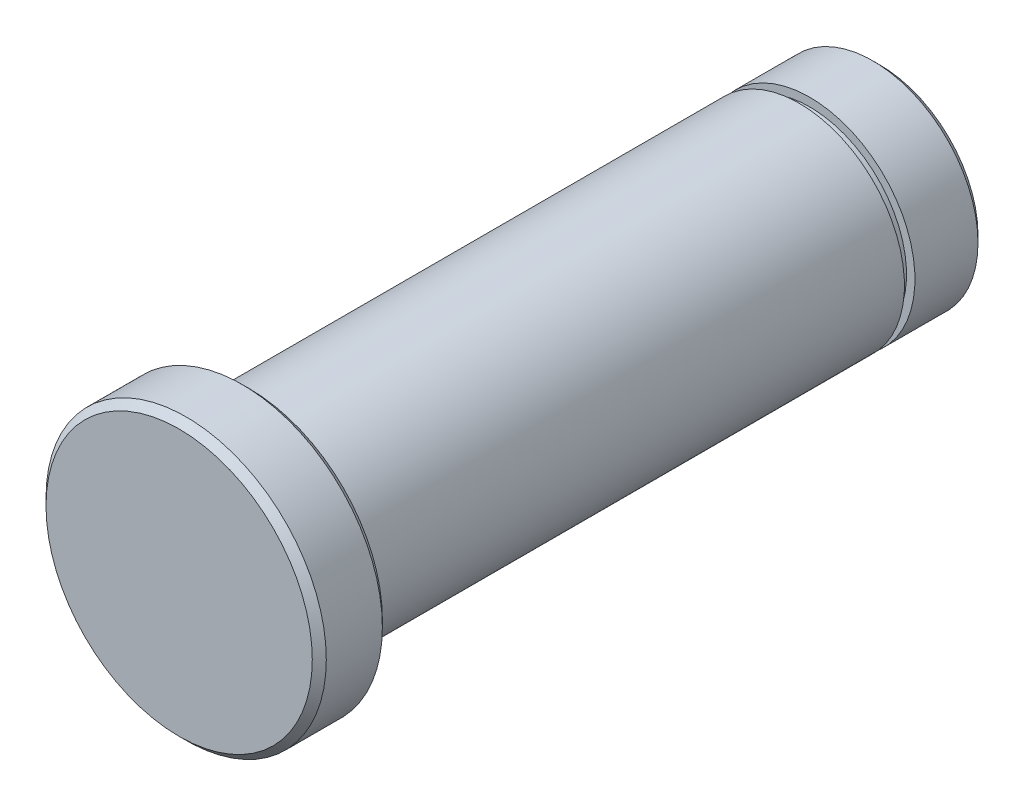
SolidWorks part; units mm, degrees
ref_plane "前视基准面" through (0, 0, 0) normal (0, 0, 1) x (1, 0, 0)
ref_plane "上视基准面" through (0, 0, 0) normal (0, 1, 0) x (1, 0, 0)
ref_plane "右视基准面" through (0, 0, 0) normal (1, 0, 0) x (0, 0, -1)
sketch "草图1" plane through (0, 0, 0) normal (0, 0, 1) x (1, 0, 0)
  circle A0 centre (0, 0) radius 15
  dimension "D1" = 30
extrude "凸台-拉伸1" add sketch "草图1" along normal blind 90
sketch "草图2" plane through (0, 0, 90) normal (0, 0, 1) x (1, 0, 0)
  circle A0 centre (0, 0) radius 20
  dimension "D1" = 40
extrude "凸台-拉伸2" add sketch "草图2" along normal blind 10
sketch "草图3" plane through (0, 0, 0) normal (0, 1, 0) x (1, 0, 0)
  line L0 (0, 0) -> (0, -110.0499) construction
  line L2 (-17.8321, -10) -> (-13.8, -10)
  line L3 (-17.8321, -10) -> (-17.8321, -11.5)
  line L4 (-17.8321, -11.5) -> (-13.8, -11.5)
  line L5 (-13.8, -10) -> (-13.8, -11.5)
  line L6 (15, 0) -> (-15, 0) construction
  dimension "D1" = 1.5
  dimension "D3" = 13.8
  dimension "D4" = 10
revolve "切除-旋转1" cut sketch "草图3" angle 360 about L0
chamfer "倒角1" distance 1 angle 45 3 edges at (15, 0, 0) (20, 0, 100) (20, 0, 90)
